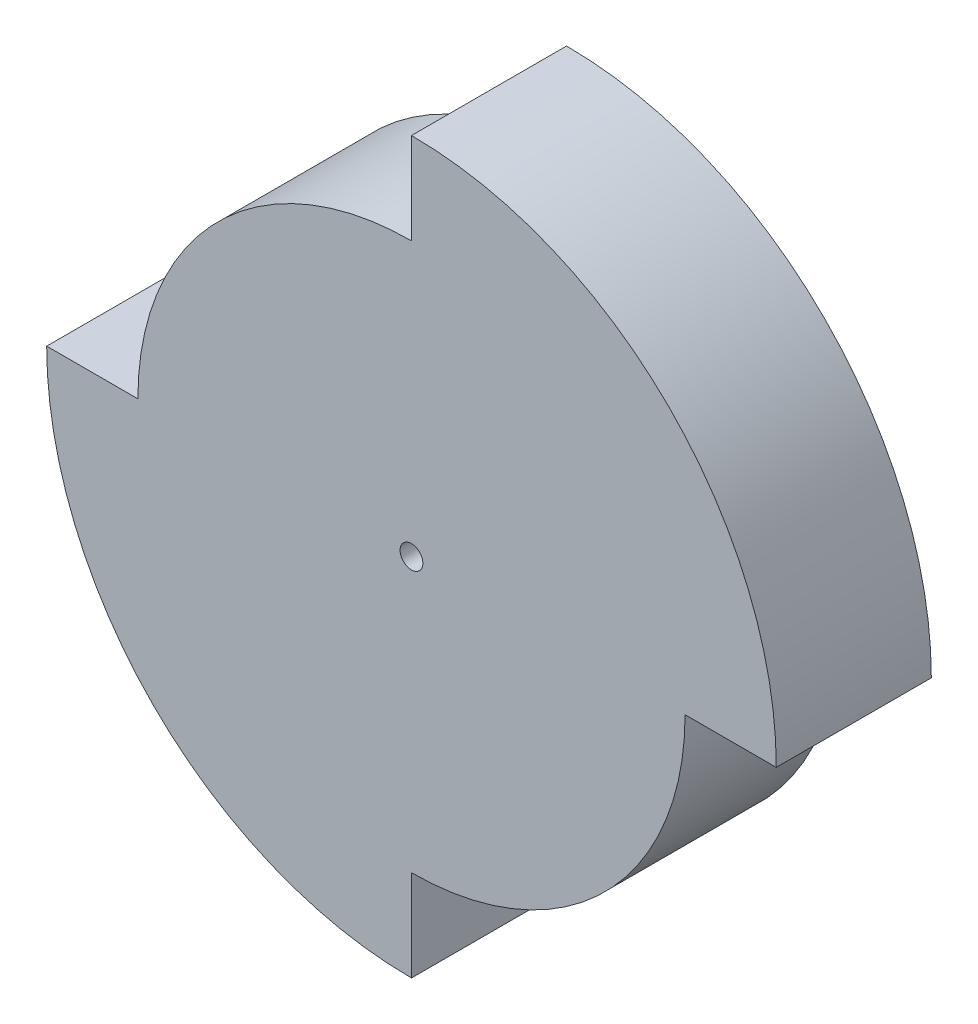
SolidWorks part; units mm, degrees
ref_plane "Plan de face" through (0, 0, 0) normal (0, 0, 1) x (1, 0, 0)
ref_plane "Plan de dessus" through (0, 0, 0) normal (0, 1, 0) x (1, 0, 0)
ref_plane "Plan de droite" through (0, 0, 0) normal (1, 0, 0) x (0, 0, -1)
sketch "Esquisse1" plane through (0, 0, 0) normal (0, 0, 1) x (1, 0, 0)
  line L0 (0, 30) -> (0, 40)
  line L1 (30, 0) -> (40, 0)
  line L2 (0, -30) -> (0, -40)
  line L3 (-30, 0) -> (-40, 0)
  circle A0 centre (0, 0) radius 30
  arc A1 (0, 40) -> (40, 0) centre (0, 0) cw
  arc A2 (-40, 0) -> (0, -40) centre (0, 0) ccw
  dimension "D1" = 60
  dimension "D2" = 10
  dimension "D3" = 10
  dimension "D4" = 10
  dimension "D5" = 10
extrude "Boss.-Extru.1" add sketch "Esquisse1" along normal blind 17 contours A0 | A1 L0 A0 L1 | L3 A2 L2 A0
sketch "Esquisse2" plane through (0, 0, 17) normal (0, 0, 1) x (1, 0, 0)
  circle A0 centre (0, 0) radius 1.25
  dimension "D1" = 2.5
extrude "Enlèv. mat.-Extru.1" cut sketch "Esquisse2" against normal blind 100
